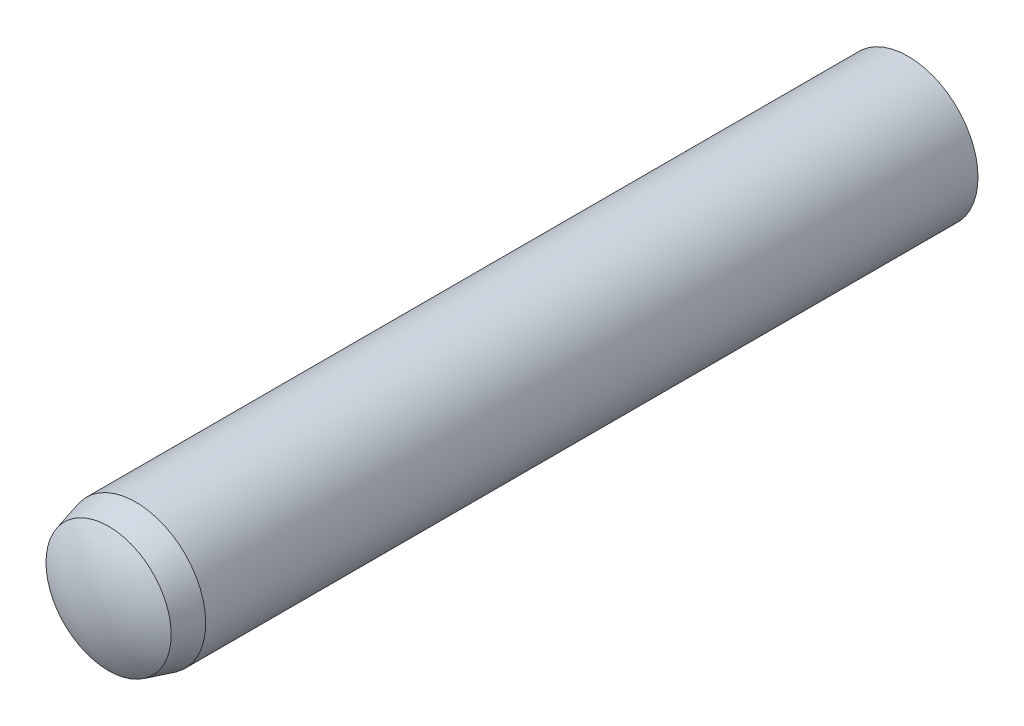
SolidWorks part; units mm, degrees
ref_plane "Front Plane" through (0, 0, 0) normal (0, 0, 1) x (1, 0, 0)
ref_plane "Top Plane" through (0, 0, 0) normal (0, 1, 0) x (1, 0, 0)
ref_plane "Right Plane" through (0, 0, 0) normal (1, 0, 0) x (0, 0, -1)
sketch "Sketch1" plane through (0, 0, 0) normal (0, 0, 1) x (1, 0, 0)
  circle A0 centre (0, 0) radius 1.5
  point P3 (0, 1.5)
  dimension "Diameter" = 3
sketch "Sketch2" plane through (0, 0, 0) normal (1, 0, 0) x (0, 0, -1)
  line L0 (-9, 0) -> (9, 0) construction
  line L1 (-9, 0) -> (-9, 1.5) construction
  line L2 (-9, 1.5) -> (9, 1.5)
  line L3 (9, 1.5) -> (9, 0) construction
  line L4 (-8.61, 1.3432) -> (-8.025, 1.5)
  arc A0 (-9, 0) -> (-8.61, 1.3432) centre (-6.4918, 0) cw
  arc A1 (9, 0) -> (8.55, 1.5) centre (6.275, 0) ccw
  point P2 (0, 0)
  point P11 (-6, 0)
  point P13 (6, 0)
  dimension "Length" = 18
  dimension "D1" = 15
  dimension "D2" = 0.45
  dimension "D3" = 0.975
  dimension "D4" = 0.585
  dimension "D5" = 3
  dimension "D6" = 3
sketch "Sketch3" plane through (0, 0, 0) normal (1, 0, 0) x (0, 0, -1)
  line L0 (-9, 0) -> (9, 0) construction
  line L1 (-8.61, 1.3432) -> (-8.025, 1.5) construction
  line L2 (-9, 0) -> (9, 0)
  line L3 (-8.61, 1.3432) -> (-8.025, 1.5)
  line L4 (-8.025, 1.5) -> (8.55, 1.5)
  arc A0 (9, 0) -> (8.55, 1.5) centre (6.275, 0) ccw construction
  arc A1 (-8.61, 1.3432) -> (-9, 0) centre (-6.4918, 0) ccw construction
  arc A2 (9, 0) -> (8.55, 1.5) centre (6.275, 0) ccw
  arc A3 (-8.61, 1.3432) -> (-9, 0) centre (-6.4918, 0) ccw
revolve "Revolve1" add sketch "Sketch3" angle 360 about L2
equation "\"D2@Sketch2\" = \"Diameter@Sketch1\" * .15"
equation "\"D3@Sketch2\" = \"Diameter@Sketch1\" * .325"
equation "\"D4@Sketch2\" = \"D3@Sketch2\" * .6"
equation "\"D5@Sketch2\"=\"Diameter@Sketch1\""
equation "\"D6@Sketch2\"=\"D5@sketch2\""
